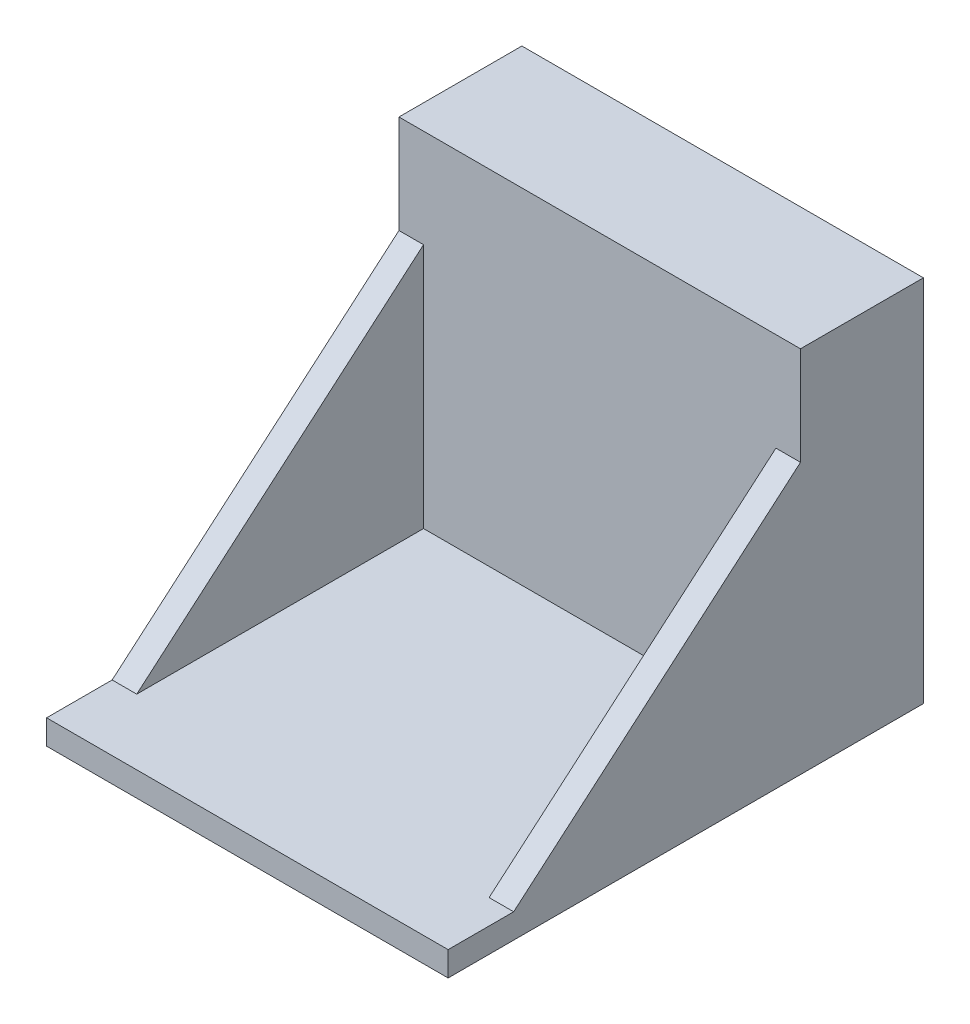
SolidWorks part; units mm, degrees
ref_plane "Front Plane" through (0, 0, 0) normal (0, 0, 1) x (1, 0, 0)
ref_plane "Top Plane" through (0, 0, 0) normal (0, 1, 0) x (1, 0, 0)
ref_plane "Right Plane" through (0, 0, 0) normal (1, 0, 0) x (0, 0, -1)
sketch "Sketch1" plane through (0, 0, 0) normal (0, 0, 1) x (1, 0, 0)
  line L1 (-26.9022, 22.8668) -> (22.0978, 22.8668)
  line L2 (-26.9022, 22.8668) -> (-26.9022, -22.1332)
  line L3 (-26.9022, -22.1332) -> (22.0978, -22.1332)
  line L4 (22.0978, 22.8668) -> (22.0978, -22.1332)
  dimension "D1" = 49
  dimension "D2" = 45
extrude "Boss-Extrude1" add sketch "Sketch1" along normal blind 15
sketch "Sketch2" plane through (0, 0, 15) normal (0, 0, 1) x (1, 0, 0)
  line L0 (22.0978, -22.1332) -> (22.0978, 22.8668) construction
  line L1 (-26.9022, -22.1332) -> (22.0978, -22.1332)
  line L2 (-26.9022, -22.1332) -> (-26.9022, -19.1332)
  line L3 (-26.9022, -19.1332) -> (22.0978, -19.1332)
  line L4 (22.0978, -22.1332) -> (22.0978, -19.1332)
  dimension "D1" = 3
extrude "Boss-Extrude2" add sketch "Sketch2" along normal blind 43
sketch "Sketch4" plane through (-26.9022, 0, 0) normal (-1, 0, 0) x (0, 0, 1)
  line L0 (15, -19.1332) -> (15, 10.8668)
  line L1 (15, 22.8668) -> (15, -19.1332) construction
  line L2 (15, 10.8668) -> (50, -19.1332)
  line L3 (58, -19.1332) -> (15, -19.1332) construction
  line L4 (50, -19.1332) -> (15, -19.1332)
  dimension "D1" = 30
  dimension "D2" = 35
extrude "Boss-Extrude3" add sketch "Sketch4" against normal blind 3
sketch "Sketch5" plane through (22.0978, 0, 0) normal (1, 0, 0) x (0, 0, -1)
  line L0 (-15, -19.1332) -> (-15, 10.8668)
  line L1 (-15, 10.8668) -> (-50, -19.1332)
  line L2 (-50, -19.1332) -> (-15, -19.1332)
extrude "Boss-Extrude4" add sketch "Sketch5" against normal blind 3
